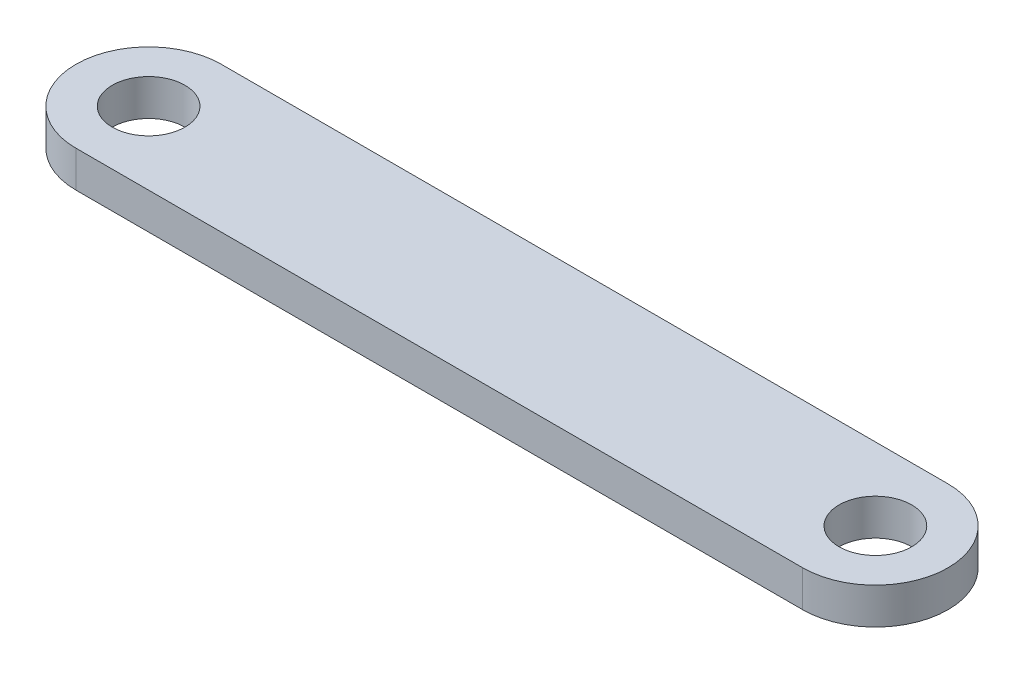
SolidWorks part; units mm, degrees
ref_plane "Ön Düzlem" through (0, 0, 0) normal (0, 0, 1) x (1, 0, 0)
ref_plane "Üst Düzlem" through (0, 0, 0) normal (0, 1, 0) x (1, 0, 0)
ref_plane "Sağ Düzlem" through (0, 0, 0) normal (1, 0, 0) x (0, 0, -1)
sketch "Sketch1" plane through (0, 0, 0) normal (0, 1, 0) x (1, 0, 0)
  line L0 (-50, 0) -> (50, 0) construction
  line L1 (-50, 10) -> (50, 10)
  line L2 (-50, -10) -> (50, -10)
  arc A0 (-50, 10) -> (-50, -10) centre (-50, 0) ccw
  arc A1 (50, -10) -> (50, 10) centre (50, 0) ccw
  circle A2 centre (-50, 0) radius 5
  circle A3 centre (50, 0) radius 5
  point P2 (0, 0)
  dimension "D1" = 10
  dimension "D3" = 10
  dimension "D4" = 10
  dimension "D2" = 100
extrude "Boss-Extrude1" add sketch "Sketch1" along normal blind 5
